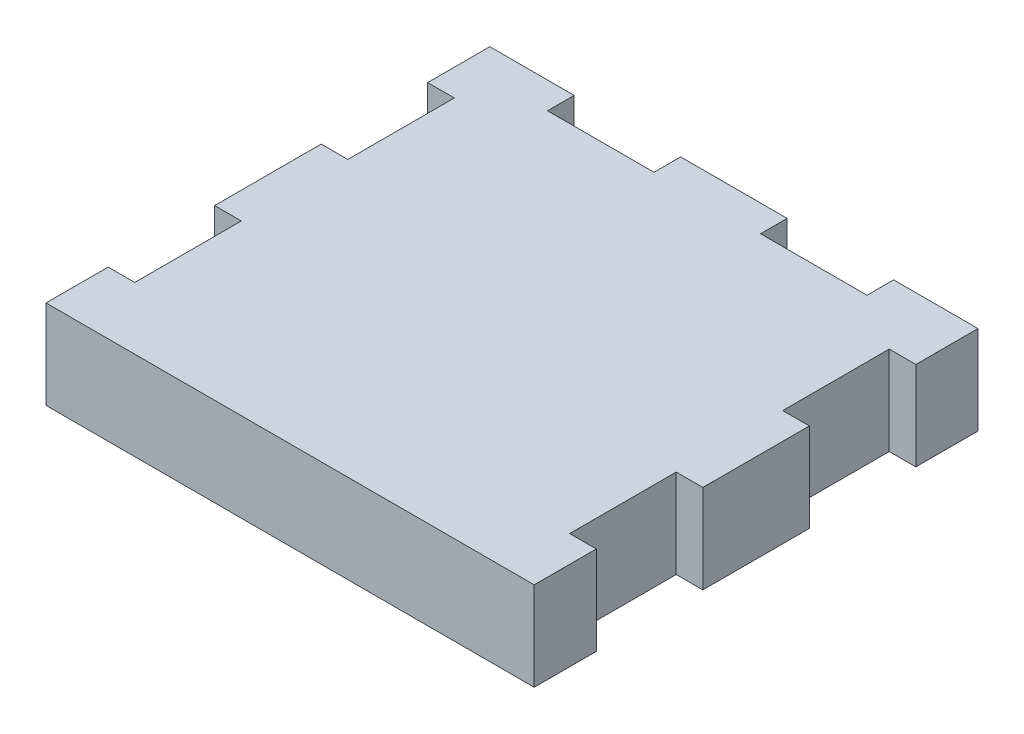
SolidWorks part; units mm, degrees
ref_plane "Front Plane" through (0, 0, 0) normal (0, 0, 1) x (1, 0, 0)
ref_plane "Top Plane" through (0, 0, 0) normal (0, 1, 0) x (1, 0, 0)
ref_plane "Right Plane" through (0, 0, 0) normal (1, 0, 0) x (0, 0, -1)
sketch "Sketch1" plane through (0, 0, 0) normal (0, 1, 0) x (1, 0, 0)
  line L30 (-135.8129, 125.7037) -> (-126.3129, 125.7037)
  line L31 (-135.8129, 125.7037) -> (-135.8129, 122.7037)
  line L33 (-126.3129, 125.7037) -> (-126.3129, 122.7037)
  line L34 (-126.3129, 122.7037) -> (-114.3129, 122.7037)
  line L35 (-135.8129, 122.7037) -> (-135.8129, 118.7037)
  line L36 (-135.8129, 118.7037) -> (-132.8129, 118.7037)
  line L37 (-80.8129, 122.7037) -> (-80.8129, 118.7037)
  line L39 (-83.8129, 118.7037) -> (-80.8129, 118.7037)
  line L40 (-114.3129, 125.7037) -> (-102.3129, 125.7037)
  line L41 (-114.3129, 125.7037) -> (-114.3129, 122.7037)
  line L43 (-102.3129, 125.7037) -> (-102.3129, 122.7037)
  line L44 (-90.3129, 125.7037) -> (-80.8129, 125.7037)
  line L45 (-90.3129, 125.7037) -> (-90.3129, 122.7037)
  line L47 (-80.8129, 125.7037) -> (-80.8129, 122.7037)
  line L49 (-132.8129, 118.7037) -> (-132.8129, 106.7037)
  line L51 (-83.8129, 118.7037) -> (-83.8129, 106.7037)
  line L52 (-135.8129, 106.7037) -> (-132.8129, 106.7037)
  line L53 (-135.8129, 106.7037) -> (-135.8129, 94.7037)
  line L54 (-135.8129, 94.7037) -> (-132.8129, 94.7037)
  line L55 (-80.8129, 106.7037) -> (-80.8129, 94.7037)
  line L57 (-132.8129, 94.7037) -> (-132.8129, 82.7037)
  line L59 (-83.8129, 94.7037) -> (-83.8129, 82.7037)
  line L60 (-135.8129, 82.7037) -> (-132.8129, 82.7037)
  line L61 (-135.8129, 82.7037) -> (-135.8129, 75.7037)
  line L62 (-135.8129, 75.7037) -> (-80.8129, 75.7037)
  line L63 (-80.8129, 82.7037) -> (-80.8129, 75.7037)
  line L64 (-83.8129, 106.7037) -> (-80.8129, 106.7037)
  line L65 (-83.8129, 94.7037) -> (-80.8129, 94.7037)
  line L66 (-83.8129, 82.7037) -> (-80.8129, 82.7037)
  line L67 (-102.3129, 122.7037) -> (-90.3129, 122.7037)
  point P13 (0, 0)
  point P15 (0, 0)
  point P17 (0, 0)
  point P19 (0, 0)
  point P262 (0, 0)
  point P264 (0, 0)
  point P266 (0, 0)
  point P270 (0, 0)
  point P271 (0, 0)
  point P272 (0, 0)
  point P273 (0, 0)
  point P274 (0, 0)
  point P275 (0, 0)
  point P276 (0, 0)
  point P277 (0, 0)
  point P278 (0, 0)
  point P279 (0, 0)
  point P280 (0, 0)
  point P281 (0, 0)
  point P282 (0, 0)
  point P283 (0, 0)
  point P284 (0, 0)
  point P285 (0, 0)
  point P286 (0, 0)
  point P287 (0, 0)
  point P288 (0, 0)
  point P289 (0, 0)
  point P290 (0, 0)
  point P291 (0, 0)
  point P292 (0, 0)
  point P293 (0, 0)
  point P294 (0, 0)
  point P295 (0, 0)
  point P296 (0, 0)
  point P297 (0, 0)
  point P298 (0, 0)
  point P299 (0, 0)
  point P300 (0, 0)
  point P301 (0, 0)
  point P302 (0, 0)
  point P303 (0, 0)
  point P304 (0, 0)
extrude "Boss-Extrude1" add sketch "Sketch1" along normal blind 10 separate body
